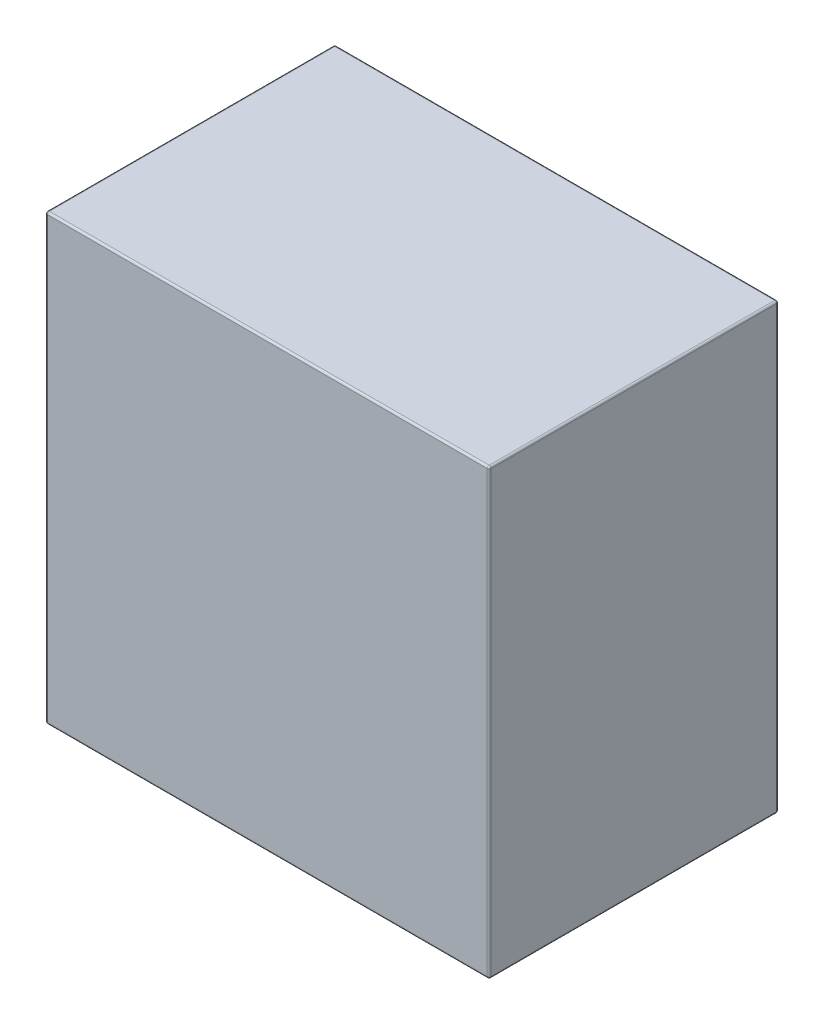
SolidWorks part; units mm, degrees
ref_plane "Front Plane" through (0, 0, 0) normal (1, 0, 0) x (0, 1, 0)
ref_plane "Top Plane" through (0, 0, 0) normal (0, 0, 1) x (0, 1, 0)
ref_plane "Right Plane" through (0, 0, 0) normal (0, 1, 0) x (-1, 0, 0)
sketch "Sketch1" plane through (0, 0, 0) normal (0, 0, 1) x (0, 1, 0)
  line L1 (-11.5, -11.5) -> (11.5, -11.5)
  line L2 (-11.5, -11.5) -> (-11.5, 11.5)
  line L3 (-11.5, 11.5) -> (11.5, 11.5)
  line L4 (11.5, -11.5) -> (11.5, 11.5)
  line L5 (-11.5, -11.5) -> (11.5, 11.5) construction
  line L6 (-11.5, 11.5) -> (11.5, -11.5) construction
  point P0 (0, 0)
  dimension "D1" = 23
  dimension "D2" = 23
extrude "Boss-Extrude1" add sketch "Sketch1" along normal blind 15
fillet "Fillet1" radius 0.1 12 edges at (-11.5, 11.5, 7.5) (-11.5, -11.5, 7.5) (11.5, -11.5, 7.5) (11.5, 11.5, 7.5) (11.5, 0, 15) (0, -11.5, 15) (-11.5, 0, 15) (0, 11.5, 15) (11.5, 0, 0) (0, -11.5, 0) (-11.5, 0, 0) (0, 11.5, 0)
